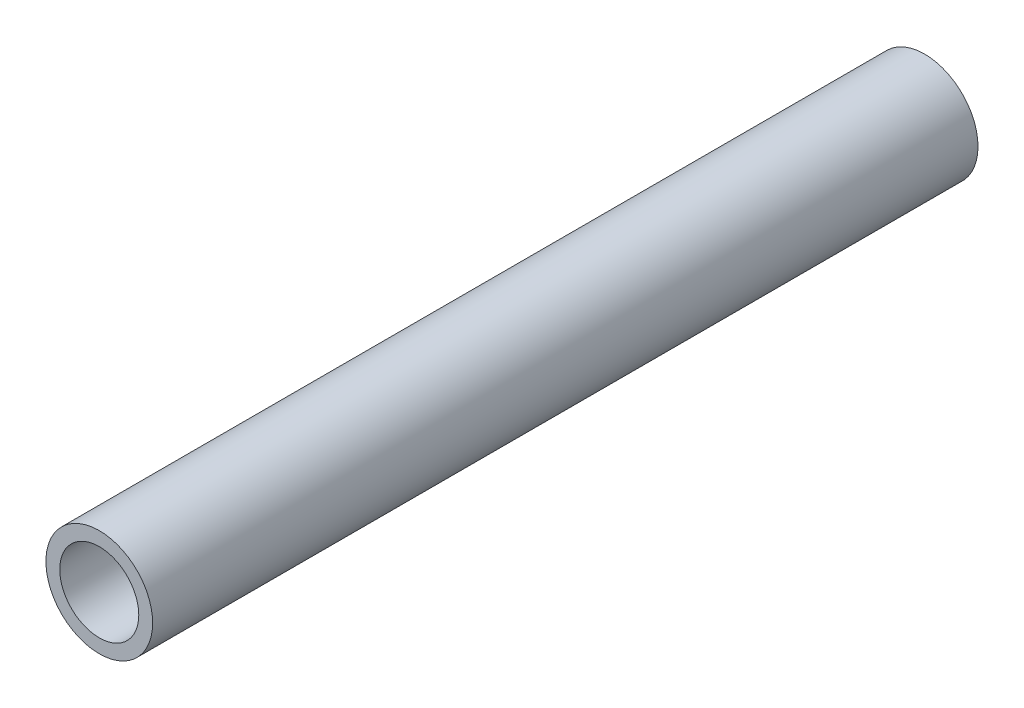
SolidWorks part; units mm, degrees
ref_plane "Front Plane" through (0, 0, 0) normal (0, 0, 1) x (1, 0, 0)
ref_plane "Top Plane" through (0, 0, 0) normal (0, 1, 0) x (1, 0, 0)
ref_plane "Right Plane" through (0, 0, 0) normal (1, 0, 0) x (0, 0, -1)
sketch "Sketch1" plane through (0, 0, 0) normal (0, 0, 1) x (1, 0, 0)
  circle A0 centre (0, 0) radius 10.668
  dimension "Pipe OD" = 21.336
extrude "Extrude-Thin1" add sketch "Sketch1" along normal mid plane 165 thin thin type one direction reverse wall 2.7686
